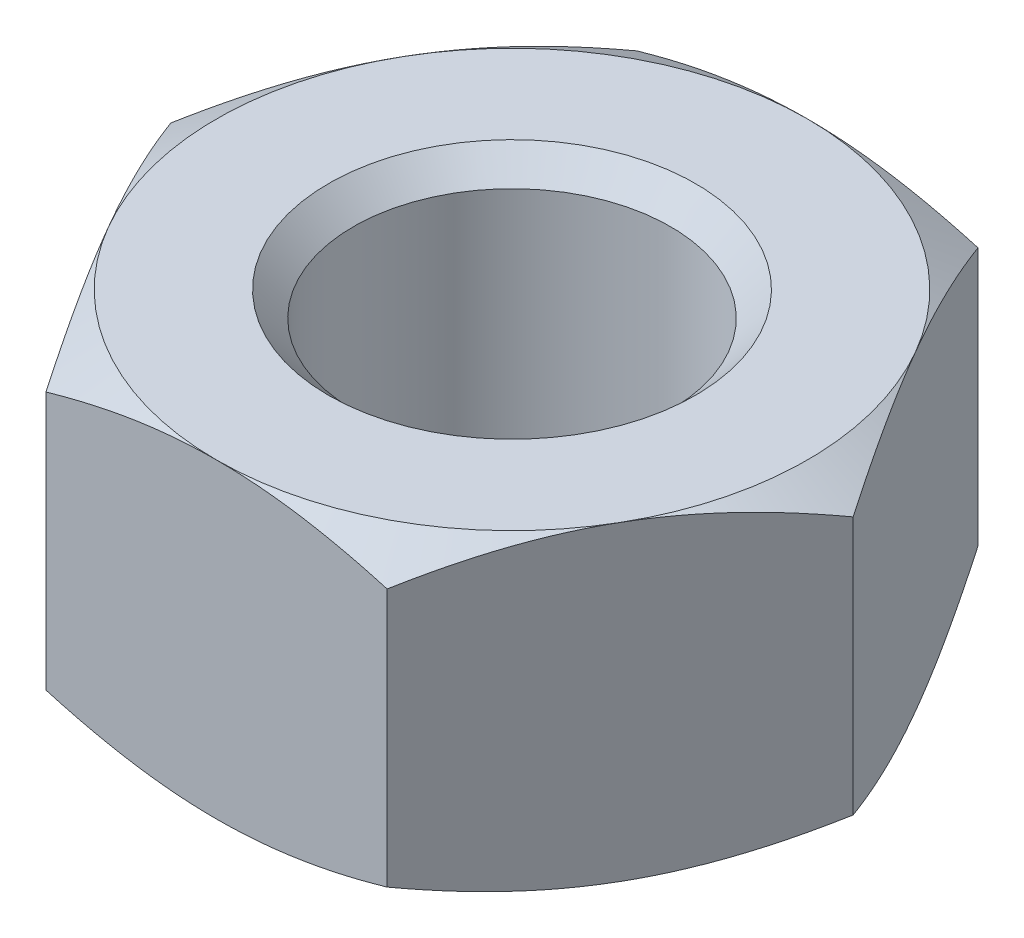
SolidWorks part; units mm, degrees
ref_plane "///// FRONT XY /////" through (0, 0, 0) normal (0, 0, 1) x (1, 0, 0)
ref_plane "| | | | |  TOP X-Z  | | | | |" through (0, 0, 0) normal (0, 1, 0) x (1, 0, 0)
ref_plane "\\\\\\\\\\ RIGHT -ZY \\\\\\\\\\" through (0, 0, 0) normal (1, 0, 0) x (0, 0, -1)
sketch3d "AXES"
  line L0 (0, 0, 0) -> (0, 0, 100) construction
  line L1 (0, 0, 0) -> (0, 100, 0) construction
  line L2 (0, 0, 0) -> (100, 0, 0) construction
  line L3 (0, 0, 0) -> (0, 0, -100) construction
  line L4 (0, 0, 0) -> (0, -100, 0) construction
  line L5 (0, 0, 0) -> (-100, 0, 0) construction
  dimension "D1" = 100
ref_plane "FRONT X,Y" through (0, 0, 0) normal (0, 0, 1) x (1, 0, 0)
ref_plane "TOP X,-Z" through (0, 0, 0) normal (0, 1, 0) x (1, 0, 0)
ref_plane "RIGHT -Z,Y" through (0, 0, 0) normal (1, 0, 0) x (0, 0, -1)
sketch "Sketch1" plane through (0, 0, 0) normal (0, 1, 0) x (1, 0, 0)
  line L1 (5.4848, 9.5) -> (-5.4848, 9.5)
  line L2 (-5.4848, 9.5) -> (-10.9697, 0)
  line L3 (-10.9697, 0) -> (-5.4848, -9.5)
  line L4 (-5.4848, -9.5) -> (5.4848, -9.5)
  line L5 (5.4848, -9.5) -> (10.9697, 0)
  line L6 (10.9697, 0) -> (5.4848, 9.5)
  circle A0 centre (0, 0) radius 9.5 construction
  dimension "D1" = 19
extrude "Boss-Extrude1" add sketch "Sketch1" along normal blind 10
sketch "Sketch3" plane through (0, 0, 0) normal (0, 0, 1) x (1, 0, 0)
  line L0 (9.5, 10) -> (10.9697, 10)
  line L1 (5.4848, 10) -> (10.9697, 10) construction
  line L2 (10.9697, 10) -> (10.9697, 9.1515)
  line L3 (10.9697, 9.1515) -> (9.5, 10)
  line L4 (10.9697, 5) -> (-10.9697, 5) construction
  line L5 (0, 10) -> (0, 0) construction
  line L6 (-5.4848, 10) -> (5.4848, 10) construction
  line L7 (10.9697, 10) -> (10.9697, 0) construction
  line L8 (-10.9697, 10) -> (-10.9697, 0) construction
  line L9 (10.9697, 0.8485) -> (9.5, 0)
  line L10 (10.9697, 0) -> (10.9697, 0.8485)
  line L11 (9.5, 0) -> (10.9697, 0)
  dimension "D1" = 30
  dimension "D2" = 9.5
revolve "Cut-Revolve1" cut sketch "Sketch3" angle 360 about L5
hole_wizard "M12 Tapped Hole1" positions "Sketch5" profile "Sketch4" tap size "M12" standard "DIN" end condition through all
sketch "Sketch5" plane through (0, 10, 0) normal (0, 1, 0) x (1, 0, 0)
  point P0 (0, 0)
sketch "Sketch4" plane through (0, 10, 0) normal (1, 0, 0) x (0, 0, 1)
  line L0 (0, 0) -> (0, 10)
  line L1 (0, 10) -> (5.1, 10)
  line L2 (5.1, 10) -> (5.1, 0)
  line L5 (5.1, 0) -> (0, 0)
  line L11 (0, -6.35) -> (0, 107.95) construction
  dimension "Thru Tap Drill Dia." = 10.2
  dimension "Thru Tap Drill Depth" = 10
cosmetic thread "Hole Thread1" parameters "D2"=12
chamfer "Chamfer1" distance 0.8 angle 45 2 edges at (0, 0, 5.1) (0, 10, 5.1)
equation "\"W\"= 19"
equation "\"H\"= 10"
equation "\"D1@Boss-Extrude1\" = \"H\""
equation "\"D2@Sketch3\"=\"W\"/2"
equation "\"D1@Sketch1\" = \"W\""
